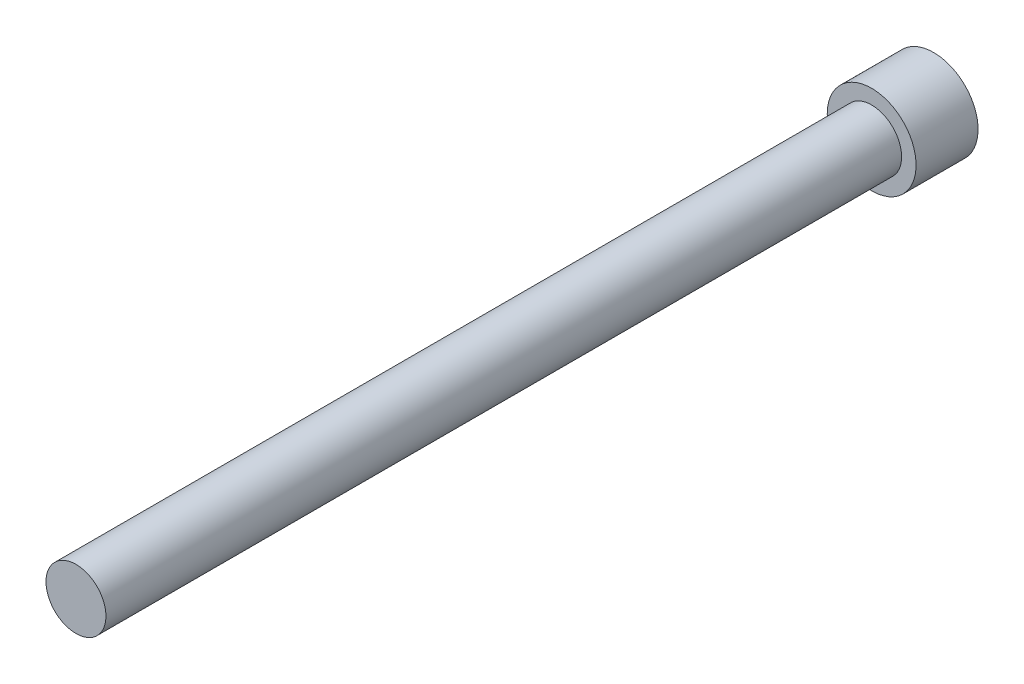
SolidWorks part; units mm, degrees
ref_plane "Front Plane" through (0, 0, 0) normal (0, 0, 1) x (1, 0, 0)
ref_plane "Top Plane" through (0, 0, 0) normal (0, 1, 0) x (1, 0, 0)
ref_plane "Right Plane" through (0, 0, 0) normal (1, 0, 0) x (0, 0, -1)
sketch "Sketch1" plane through (0, 0, 0) normal (0, 0, 1) x (1, 0, 0)
  circle A0 centre (0, 0) radius 1.45
  dimension "D1" = 2.9
extrude "Boss-Extrude1" add sketch "Sketch1" along normal blind 41.5
sketch "Sketch2" plane through (0, 0, 0) normal (0, 0, -1) x (-1, 0, 0)
  circle A0 centre (0, 0) radius 2.15
  dimension "D1" = 4.3
extrude "Boss-Extrude2" add sketch "Sketch2" against normal blind 3
